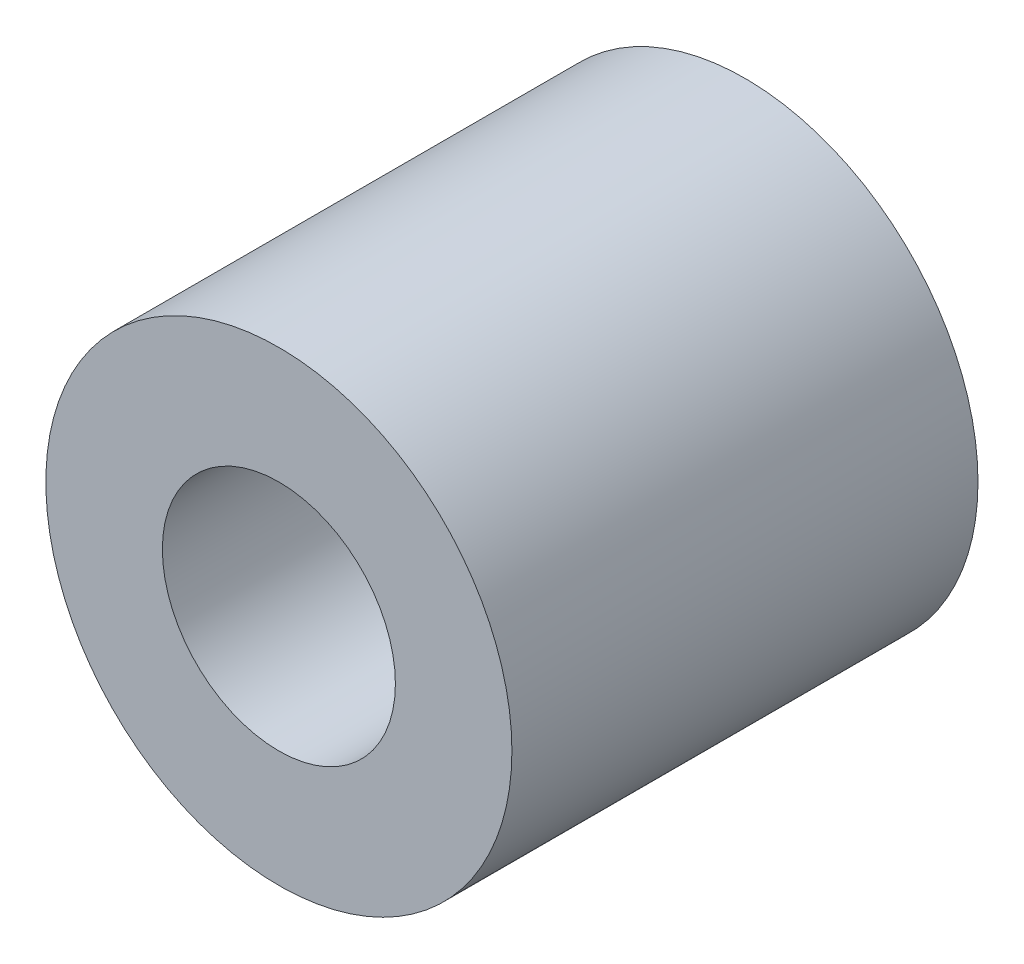
SolidWorks part; units mm, degrees
material "BUTYL"
ref_plane "Front Plane" through (0, 0, 0) normal (0, 0, 1) x (1, 0, 0)
ref_plane "Top Plane" through (0, 0, 0) normal (0, 1, 0) x (1, 0, 0)
ref_plane "Right Plane" through (0, 0, 0) normal (1, 0, 0) x (0, 0, -1)
sketch "Sketch1" plane through (0, 0, 0) normal (0, 1, 0) x (1, 0, 0)
  line L0 (0, 0) -> (0, -6)
  dimension "D1" = 6
ref_plane "Plane2" through (0, 0, 6) normal (0, 0, 1) x (1, 0, 0)
sketch "Sketch2" plane through (0, 0, 6) normal (0, 0, 1) x (1, 0, 0)
  circle A0 centre (0, 0) radius 1.5
  circle A1 centre (0, 0) radius 3
  dimension "D1" = 3
  dimension "D2" = 6
sweep "Sweep1" add profiles "Sketch2" path "Sketch1"
